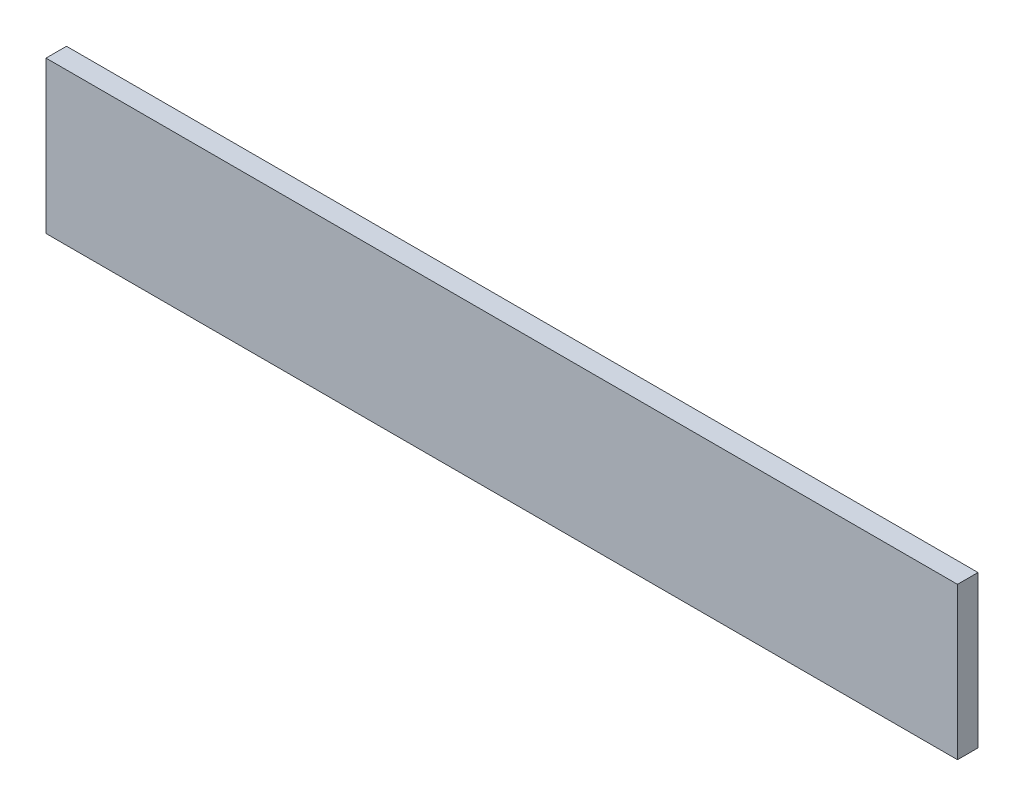
SolidWorks part; units mm, degrees
ref_plane "Front" through (0, 0, 0) normal (0, 0, 1) x (1, 0, 0)
ref_plane "Top" through (0, 0, 0) normal (0, 1, 0) x (1, 0, 0)
ref_plane "Right" through (0, 0, 0) normal (1, 0, 0) x (0, 0, -1)
sketch "Esquisse1" plane through (0, 0, 0) normal (0, 0, 1) x (1, 0, 0)
  line L1 (0, 0) -> (1200, 0)
  line L2 (0, 0) -> (0, 200)
  line L3 (0, 200) -> (1200, 200)
  line L4 (1200, 0) -> (1200, 200)
  dimension "D1" = 1200
  dimension "D2" = 200
extrude "Boss.-Extru.1" add sketch "Esquisse1" along normal blind 27
